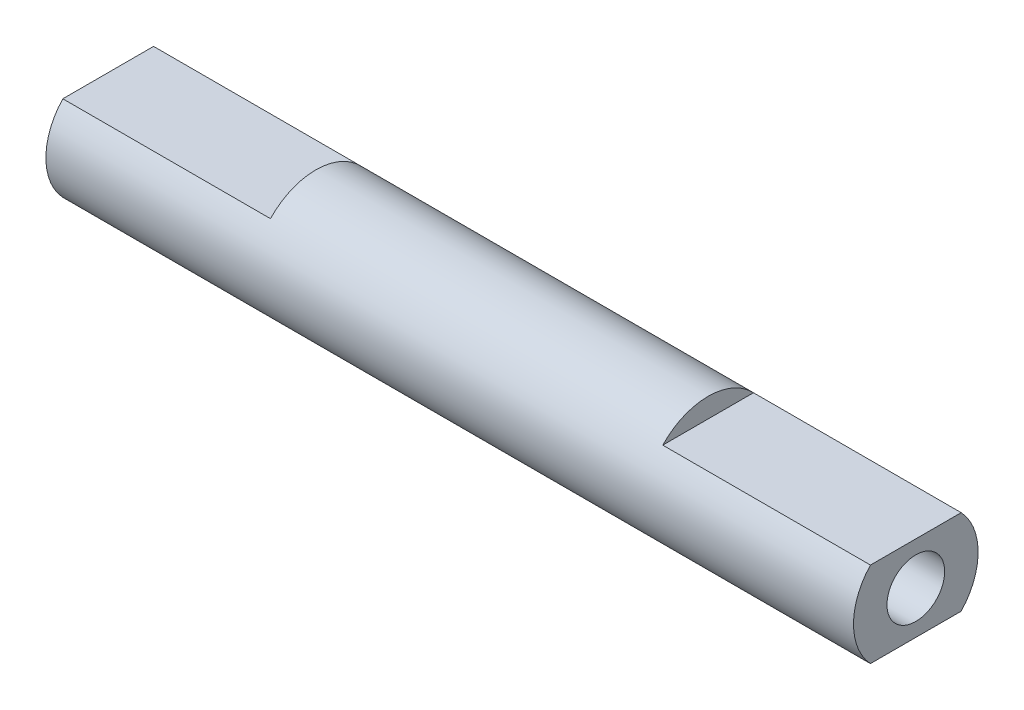
SolidWorks part; units mm, degrees
ref_plane "Front Plane" through (0, 0, 0) normal (0, 0, 1) x (1, 0, 0)
ref_plane "Top Plane" through (0, 0, 0) normal (0, 1, 0) x (1, 0, 0)
ref_plane "Right Plane" through (0, 0, 0) normal (1, 0, 0) x (0, 0, -1)
sketch "Sketch1" plane through (0, 0, 0) normal (1, 0, 0) x (0, 0, -1)
  circle A0 centre (0, 0) radius 2.7
  dimension "D1" = 5.4
extrude "Boss-Extrude1" add sketch "Sketch1" along normal blind 35
sketch "Sketch2" plane through (0, 0, 0) normal (0, 0, 1) x (1, 0, 0)
  line L0 (17.5, -2.7) -> (17.5, 2.7) construction
  line L1 (35, 2.7) -> (26, 2.7)
  line L2 (35, 2.7) -> (35, 1.85)
  line L3 (35, 1.85) -> (26, 1.85)
  line L4 (26, 2.7) -> (26, 1.85)
  line L5 (35, -2.7) -> (26, -2.7)
  line L6 (35, -2.7) -> (35, -1.85)
  line L7 (35, -1.85) -> (26, -1.85)
  line L8 (26, -2.7) -> (26, -1.85)
  line L9 (0, -2.7) -> (35, -2.7) construction
  line L10 (35, 2.7) -> (0, 2.7) construction
  line L11 (9, -2.7) -> (9, -1.85)
  line L12 (0, -1.85) -> (9, -1.85)
  line L13 (0, -2.7) -> (0, -1.85)
  line L14 (0, -2.7) -> (9, -2.7)
  line L15 (9, 2.7) -> (9, 1.85)
  line L16 (0, 1.85) -> (9, 1.85)
  line L17 (0, 2.7) -> (0, 1.85)
  line L18 (0, 2.7) -> (9, 2.7)
  dimension "D1" = 3.7
  dimension "D2" = 9
extrude "Cut-Extrude1" cut sketch "Sketch2" against normal through all both and the other way through all
hole_wizard "M3 Tapped Hole1" positions "Sketch3" profile "Sketch4" tap size "M3" standard "ISO"
sketch "Sketch3" plane through (35, 0, 0) normal (1, 0, 0) x (0, 0, -1)
  point P0 (0, 0)
sketch "Sketch4" plane through (35, 0, 0) normal (0, 1, 0) x (0, 0, -1)
  line L0 (0, 0) -> (0, 8.2511)
  line L1 (0, 8.2511) -> (1.25, 7.5)
  line L2 (1.25, 7.5) -> (1.25, 0)
  line L5 (1.25, 0) -> (0, 0)
  line L10 (0, 8.2511) -> (-1.25, 7.5) construction
  line L11 (0, -6.35) -> (0, 107.95) construction
  dimension "Tap Drill Dia." = 2.5
  dimension "Tap Drill Depth" = 7.5
  dimension "Drill Angle" = 118
cosmetic thread "Hole Thread1" parameters "D1"=6, "D2"=3
